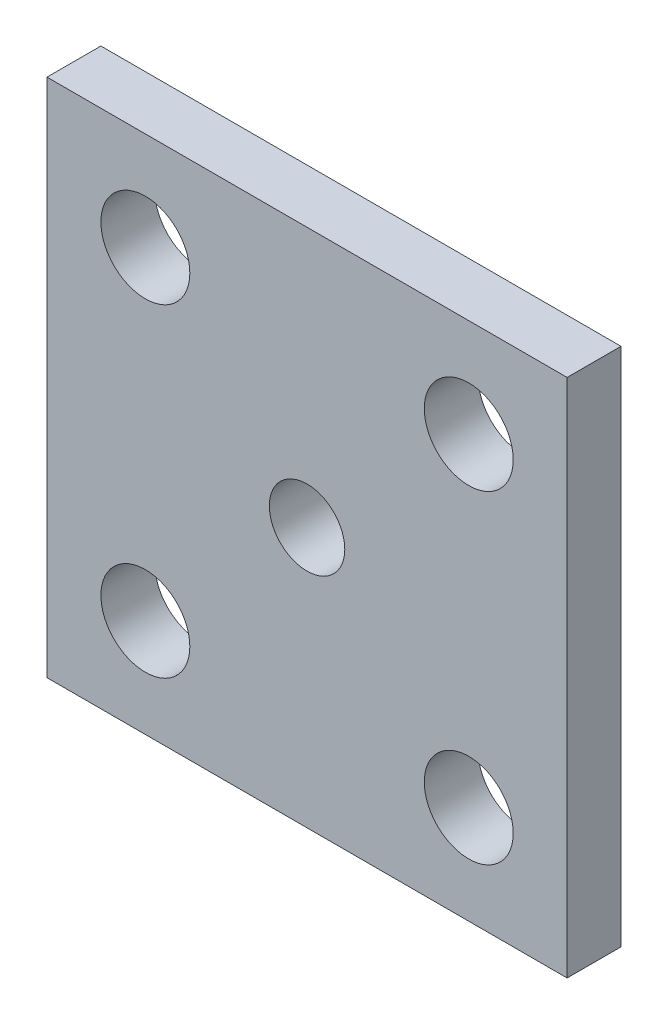
SolidWorks part; units mm, degrees
material "Acrylic (Medium-high impact)"
ref_plane "Front Plane" through (0, 0, 0) normal (0, 0, 1) x (1, 0, 0)
ref_plane "Top Plane" through (0, 0, 0) normal (0, 1, 0) x (1, 0, 0)
ref_plane "Right Plane" through (0, 0, 0) normal (1, 0, 0) x (0, 0, -1)
sketch "Sketch1" plane through (0, 0, 0) normal (0, 0, 1) x (1, 0, 0)
  line L0 (39.125, 39.125) -> (9.125, 9.125) construction
  line L1 (0, 0) -> (48.25, 0)
  line L2 (0, 0) -> (0, 48.25)
  line L3 (0, 48.25) -> (48.25, 48.25)
  line L4 (48.25, 0) -> (48.25, 48.25)
  line L5 (9.125, 9.125) -> (39.125, 9.125) construction
  line L6 (9.125, 9.125) -> (9.125, 39.125) construction
  line L7 (9.125, 39.125) -> (39.125, 39.125) construction
  line L8 (39.125, 9.125) -> (39.125, 39.125) construction
  line L9 (5, 9.125) -> (0, 9.125) construction
  line L10 (34.8959, 1.8) -> (30.6668, 9.125)
  line L11 (17.5832, 9.125) -> (13.3541, 16.45)
  line L12 (13.3541, 16.45) -> (4.8959, 16.45)
  line L13 (4.8959, 16.45) -> (0.6668, 9.125)
  line L14 (0.6668, 9.125) -> (4.8959, 1.8)
  line L15 (4.8959, 1.8) -> (13.3541, 1.8)
  line L16 (13.3541, 1.8) -> (17.5832, 9.125)
  line L17 (43.3541, 1.8) -> (34.8959, 1.8)
  line L18 (47.5832, 9.125) -> (43.3541, 1.8)
  line L19 (43.3541, 16.45) -> (47.5832, 9.125)
  line L20 (9.125, 24.125) -> (0, 24.125) construction
  line L21 (24.125, 9.125) -> (24.125, 0) construction
  line L22 (34.8959, 16.45) -> (43.3541, 16.45)
  line L23 (30.6668, 9.125) -> (34.8959, 16.45)
  line L24 (43.3541, 31.8) -> (47.5832, 39.125)
  line L25 (47.5832, 39.125) -> (43.3541, 46.45)
  line L26 (43.3541, 46.45) -> (34.8959, 46.45)
  line L27 (34.8959, 46.45) -> (30.6668, 39.125)
  line L28 (30.6668, 39.125) -> (34.8959, 31.8)
  line L29 (34.8959, 31.8) -> (43.3541, 31.8)
  line L30 (4.8959, 31.8) -> (0.6668, 39.125)
  line L31 (0.6668, 39.125) -> (4.8959, 46.45)
  line L32 (4.8959, 46.45) -> (13.3541, 46.45)
  line L33 (13.3541, 46.45) -> (17.5832, 39.125)
  line L34 (17.5832, 39.125) -> (13.3541, 31.8)
  line L35 (13.3541, 31.8) -> (4.8959, 31.8)
  circle A0 centre (9.125, 9.125) radius 4.125
  circle A1 centre (9.125, 9.125) radius 7.325 construction
  circle A2 centre (39.125, 9.125) radius 4.125
  circle A3 centre (39.125, 39.125) radius 4.125
  circle A4 centre (24.125, 24.125) radius 3.5
  circle A5 centre (9.125, 39.125) radius 4.125
  point P47 (24.125, 39.125)
  dimension "D2" = 8.25
  dimension "D3" = 5
  dimension "D4" = 7
  dimension "D1" = 30
  dimension "D5" = 14.65
extrude "Boss-Extrude1" add sketch "Sketch1" along normal blind 5 contours L35 L34 L33 L32 L31 L30 A5 | L15 L16 L11 L12 L13 L14 A0 | L23 L10 L17 L18 L19 L22 A2 | L28 L29 L24 L25 L26 L27 A3 | L1 L4 L3 L2 A4 L10 L23 L22 L19 L18 L17 L16 L15 L14 L13 L12 L11 L29 L28 L27 L26 L25 L24 L34 L35 L30 L31 L32 L33
